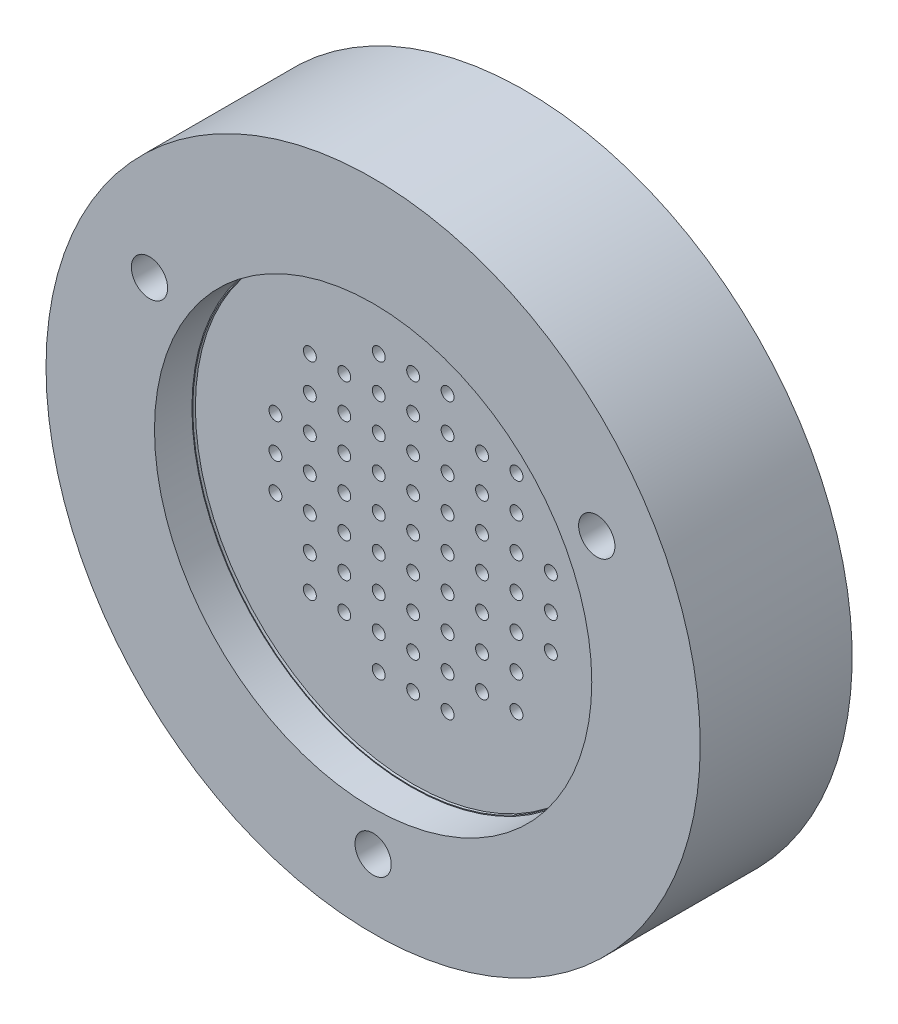
SolidWorks part; units mm, degrees
ref_plane "Plan de face" through (0, 0, 0) normal (0, 0, 1) x (1, 0, 0)
ref_plane "Plan de dessus" through (0, 0, 0) normal (0, 1, 0) x (1, 0, 0)
ref_plane "Plan de droite" through (0, 0, 0) normal (1, 0, 0) x (0, 0, -1)
sketch "Sketch1" plane through (0, 0, 0) normal (0, 0, 1) x (1, 0, 0)
  circle A0 centre (0, 0) radius 38
extrude "Boss-Extrude1" add sketch "Sketch1" along normal blind 5
sketch "Sketch2" plane through (0, 0, 5) normal (0, 0, 1) x (1, 0, 0)
  circle A0 centre (0, 0) radius 0.75
extrude "Cut-Extrude1" cut sketch "Sketch2" against normal through all
pattern_linear "LPattern1" count 5 spacing 4 along (0, 1, 0) count 5 spacing 4 along (1, 0, 0) skipping (2, 4), (3, 4), (4, 2), (4, 3), (4, 4) of "Cut-Extrude1"
mirror "Mirror1" about plane through (0, 0, 0) normal (1, 0, 0) of "LPattern1" second plane through (0, 0, 0) second plane normal (0, 1, 0)
sketch "Sketch16" plane through (0, 0, 5) normal (0, 0, 1) x (1, 0, 0)
  circle A0 centre (0, 0) radius 25.4
  circle A1 centre (0, 0) radius 38
extrude "Boss-Extrude2" add sketch "Sketch16" along normal blind 4.65
sketch "Sketch17" plane through (0, 0, 0) normal (0, 0, -1) x (-1, 0, 0)
  circle A0 centre (0, 0) radius 33
  circle A1 centre (0, 0) radius 38
extrude "Boss-Extrude3" add sketch "Sketch17" along normal blind 8
sketch "Sketch34" plane through (0, 0, 0) normal (0, 0, -1) x (-1, 0, 0)
  line L0 (0, -38) -> (0, -30)
  circle A0 centre (0, 0) radius 38 construction
hole_wizard "Hole for #4 300® SC Nuts (SP)3" positions "Sketch35" profile "Sketch36" hole size "#4-40" standard "PEM® Inch" end condition through all
sketch "Sketch35" plane through (0, 0, 0) normal (0, 0, -1) x (-1, 0, 0)
  point P0 (0, -30)
sketch "Sketch36" plane through (0, -30, 0) normal (1, 0, 0) x (0, 1, 0)
  line L0 (0, 0) -> (0, 9.65)
  line L1 (0, 9.65) -> (2.1082, 9.65)
  line L2 (2.1082, 9.65) -> (2.1082, 0)
  line L5 (2.1082, 0) -> (0, 0)
  line L11 (0, -6.35) -> (0, 107.95) construction
  dimension "Thru Hole Dia." = 4.2164
  dimension "Thru Hole Depth" = 9.65
pattern_circular "CirPattern1" count 3 over 360 about axis through (0, 0, 0) along (0, 0, 1) of "Hole for #4 300® SC Nuts (SP)3"
sketch "Sketch39" plane through (0, 0, -8) normal (0, 0, -1) x (-1, 0, 0)
  line L0 (0, -38) -> (0, -33)
  circle A0 centre (0, 0) radius 38 construction
  circle A1 centre (0, 0) radius 33 construction
hole_wizard "Hole for #4 300® SC Nuts (SP)4" positions "Sketch40" profile "Sketch41" hole size "#4-40" standard "PEM® Inch"
sketch "Sketch40" plane through (0, 0, -8) normal (0, 0, -1) x (-1, 0, 0)
  line L0 (0, -38) -> (0, -33) construction
  point P0 (0, -35.5)
sketch "Sketch41" plane through (0, -35.5, -8) normal (1, 0, 0) x (0, 1, 0)
  line L0 (0, 0) -> (0, 6.2667)
  line L1 (0, 6.2667) -> (2.1082, 5)
  line L2 (2.1082, 5) -> (2.1082, 0)
  line L5 (2.1082, 0) -> (0, 0)
  line L10 (0, 6.2667) -> (-2.1082, 5) construction
  line L11 (0, -6.35) -> (0, 107.95) construction
  dimension "Hole Dia." = 4.2164
  dimension "Hole Depth" = 5
  dimension "Drill Angle" = 118
pattern_circular "CirPattern2" count 3 over 360 about axis through (0, 0, 0) along (0, 0, 1) of "Hole for #4 300® SC Nuts (SP)4"
sketch "Sketch43" plane through (0, 0, 5) normal (0, 0, 1) x (1, 0, 0)
  circle A0 centre (0, 0) radius 25.3
  circle A1 centre (0, 0) radius 26.3
extrude "Boss-Extrude4" add sketch "Sketch43" along normal blind 0.3
